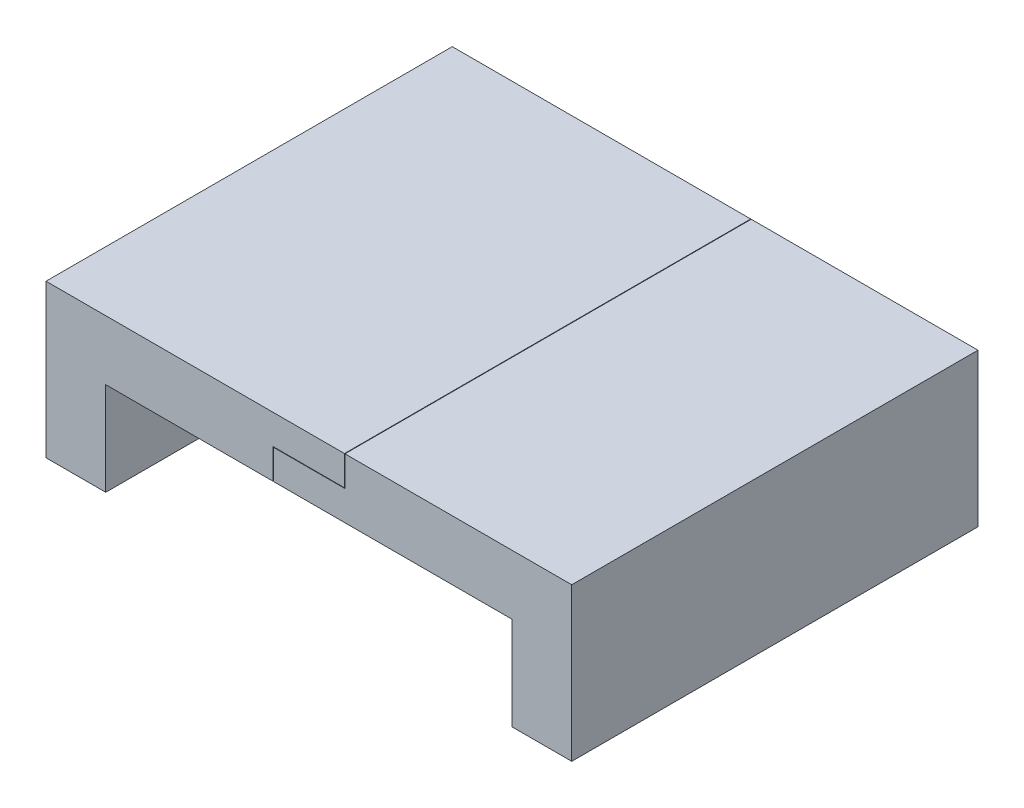
SolidWorks part; units mm, degrees
ref_plane "Front Plane" through (0, 0, 0) normal (0, 0, 1) x (1, 0, 0)
ref_plane "Top Plane" through (0, 0, 0) normal (0, 1, 0) x (1, 0, 0)
ref_plane "Right Plane" through (0, 0, 0) normal (1, 0, 0) x (0, 0, -1)
sketch "Sketch1" plane through (0, 0, 0) normal (0, 1, 0) x (1, 0, 0)
  line L1 (-139.7, 107.95) -> (139.7, 107.95)
  line L2 (-139.7, 107.95) -> (-139.7, -107.95)
  line L3 (-139.7, -107.95) -> (139.7, -107.95)
  line L4 (139.7, 107.95) -> (139.7, -107.95)
  line L5 (-139.7, 107.95) -> (139.7, -107.95) construction
  line L6 (-139.7, -107.95) -> (139.7, 107.95) construction
  point P0 (0, 0)
  dimension "D1" = 279.4
  dimension "D2" = 215.9
extrude "Boss-Extrude1" add sketch "Sketch1" along normal blind 31.75
sketch "Sketch2" plane through (0, 0, 107.95) normal (0, 0, 1) x (1, 0, 0)
  line L0 (-139.7, 31.75) -> (139.7, 31.75) construction
  line L1 (-139.7, 0) -> (-107.95, 0)
  line L2 (-139.7, 0) -> (-139.7, -49.53)
  line L3 (-139.7, -49.53) -> (-107.95, -49.53)
  line L4 (-107.95, 0) -> (-107.95, -49.53)
  line L5 (139.7, 0) -> (107.95, 0)
  line L6 (139.7, 0) -> (139.7, -49.53)
  line L7 (139.7, -49.53) -> (107.95, -49.53)
  line L8 (107.95, 0) -> (107.95, -49.53)
  dimension "D1" = 31.75
  dimension "D2" = 31.75
  dimension "D3" = 81.28
extrude "Boss-Extrude2" add sketch "Sketch2" against normal up to surface (215.9 mm away) up to face at (0, 15.875, -107.95)
sketch "Sketch3" plane through (0, 0, -107.95) normal (0, 0, -1) x (-1, 0, 0)
  line L0 (-19.05, 31.75) -> (-19.05, 15.875)
  line L1 (-139.7, 31.75) -> (139.7, 31.75) construction
  line L2 (-19.05, 15.875) -> (19.05, 15.875)
  line L3 (19.05, 15.875) -> (19.05, 0)
  line L4 (-107.95, 0) -> (107.95, 0) construction
  point P4 (0, 15.875)
  dimension "D1" = 38.1
extrude "Cut-Extrude-Thin1" cut sketch "Sketch3" against normal up to next and the other way through all thin thin type mid plane wall 0.254
sketch "Sketch4" plane through (0, 0, 0) normal (0, -1, 0) x (1, 0, 0)
  line L1 (-18.923, 107.95) -> (19.177, 107.95) construction
  line L2 (-18.923, 107.95) -> (-18.923, -107.95) construction
  line L3 (-18.923, -107.95) -> (19.177, -107.95) construction
  line L4 (19.177, 107.95) -> (19.177, -107.95) construction
  line L5 (107.95, -107.95) -> (-18.923, -107.95) construction
  line L6 (19.177, 0) -> (-18.923, 0) construction
  line L7 (0, 0) -> (0.127, 107.95) construction
  line L8 (0, 0) -> (0.127, -107.95) construction
  circle A0 centre (0, 0) radius 3
  circle A1 centre (0.1046, 88.9) radius 3
  circle A2 centre (0.1046, -88.9) radius 3
  dimension "D2" = 6
  dimension "D1" = 38.1
  dimension "D3" = 88.9
  dimension "D4" = 88.9
extrude "Cut-Extrude1" cut sketch "Sketch4" against normal blind 2
sketch "Sketch5" plane through (0, 2, 0) normal (0, -1, 0) x (-1, 0, 0)
  circle A0 centre (-0.1046, -88.9) radius 1.7
  circle A1 centre (0, 0) radius 1.7
  circle A2 centre (-0.1046, 88.9) radius 1.7
  dimension "D1" = 3.4
extrude "Cut-Extrude2" cut sketch "Sketch5" against normal blind 22.098
sketch "Sketch6" plane through (0, 16.002, 0) normal (0, -1, 0) x (1, 0, 0)
  circle A0 centre (0.1046, 88.9) radius 2.032
  circle A1 centre (0, 0) radius 2.032
  circle A2 centre (0.1046, -88.9) radius 2.032
  dimension "D1" = 4.064
extrude "Cut-Extrude3" cut sketch "Sketch6" against normal blind 6
equation "\"Thickness\"=1.25"
equation "\"D1@Boss-Extrude1\"=\"Thickness\""
equation "\"D1@Sketch2\"=\"Thickness\""
equation "\"D2@Sketch2\"=\"Thickness\""
equation "\"D1@Sketch4\"=1.5"
equation "\"D4@Sketch4\"=\"D3@Sketch4\""
equation "\"D1@Cut-Extrude2\"=22mm"
equation "\"D1@Sketch6\"=4mm"
